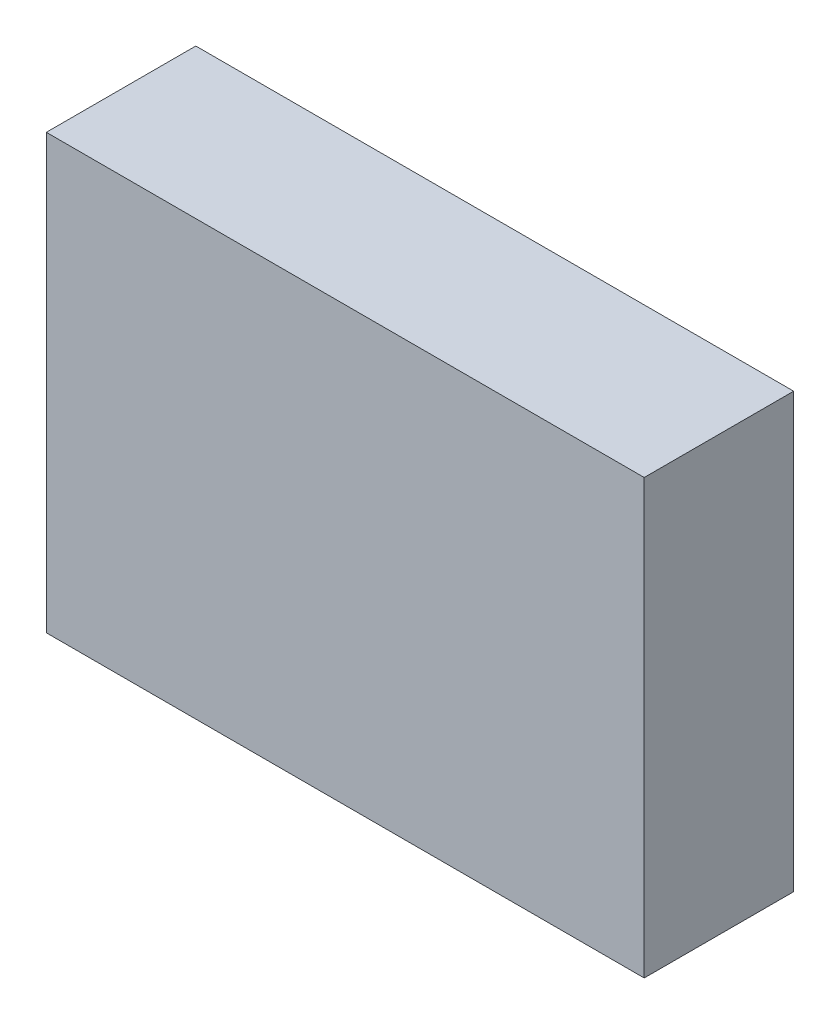
SolidWorks part; units mm, degrees
ref_plane "Front Plane" through (0, 0, 0) normal (0, 0, 1) x (1, 0, 0)
ref_plane "Top Plane" through (0, 0, 0) normal (0, 1, 0) x (1, 0, 0)
ref_plane "Right Plane" through (0, 0, 0) normal (1, 0, 0) x (0, 0, -1)
sketch "Sketch1" plane through (0, 0, 0) normal (0, 0, 1) x (1, 0, 0)
  line L1 (0, 0) -> (40, 0)
  line L2 (0, 0) -> (0, 29)
  line L3 (0, 29) -> (40, 29)
  line L4 (40, 0) -> (40, 29)
extrude "Boss-Extrude1" add sketch "Sketch1" along normal blind 10
